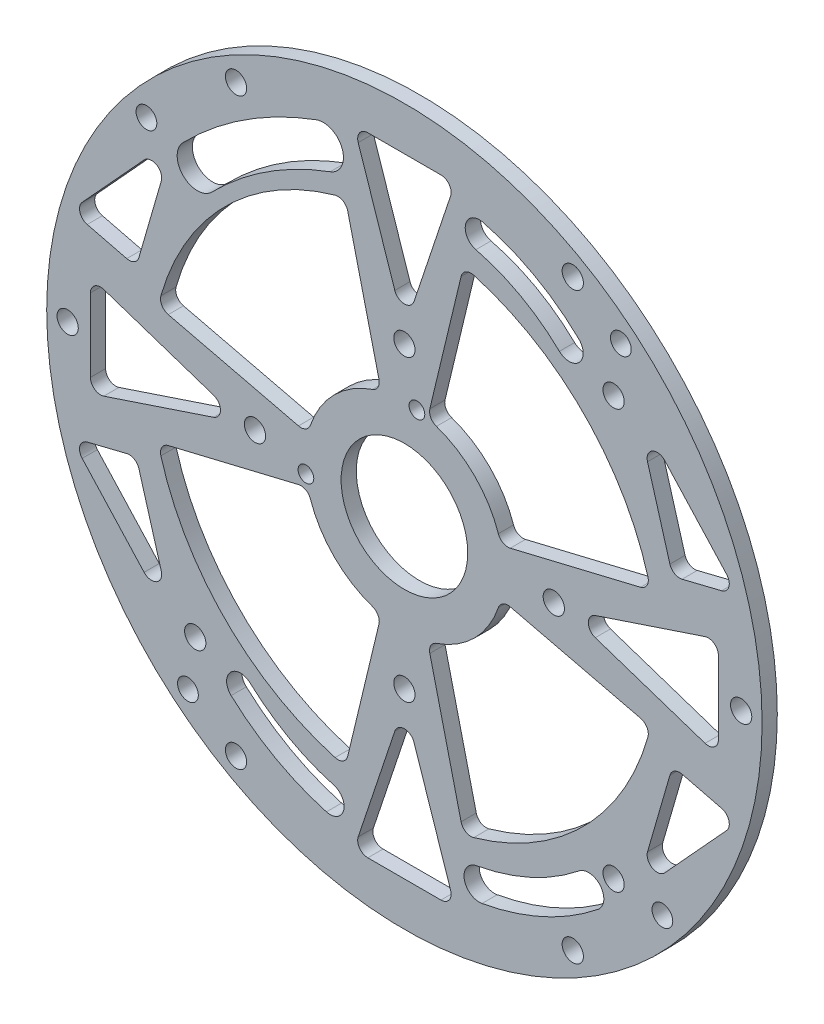
SolidWorks part; units mm, degrees
material "Hexcel AS4C (3000 丝)"
ref_plane "前视基准面" through (0, 0, 0) normal (0, 0, 1) x (1, 0, 0)
ref_plane "上视基准面" through (0, 0, 0) normal (0, 1, 0) x (1, 0, 0)
ref_plane "右视基准面" through (0, 0, 0) normal (1, 0, 0) x (0, 0, -1)
other "Configuration Table"
sketch "草图1" plane through (0, 0, 0) normal (0, 0, 1) x (1, 0, 0)
  line L0 (0, 0) -> (0, -12) construction
  line L1 (-20.8597, -20.8597) -> (20.8597, -20.8597) construction
  line L2 (-20.8597, -20.8597) -> (-20.8597, 20.8597) construction
  line L3 (-20.8597, 20.8597) -> (20.8597, 20.8597) construction
  line L4 (20.8597, -20.8597) -> (20.8597, 20.8597) construction
  line L5 (-20.8597, -20.8597) -> (20.8597, 20.8597) construction
  line L6 (-20.8597, 20.8597) -> (20.8597, -20.8597) construction
  line L7 (-14, -12) -> (14, -12) construction
  line L8 (0, 0) -> (49.95, 49.95) construction
  line L9 (0, 0) -> (70.64, 0) construction
  line L10 (0, 0) -> (0, 70.64) construction
  circle A0 centre (0, 0) radius 29.5 construction
  circle A2 centre (0, 0) radius 66.5 construction
  circle A11 centre (41.3082, 41.3082) radius 2.1
  circle A13 centre (33.25, 57.5907) radius 2.1
  circle A14 centre (66.5, 0) radius 2.1
  circle A15 centre (33.25, -57.5907) radius 2.1
  circle A16 centre (-33.25, -57.5907) radius 2.1
  circle A17 centre (-66.5, 0) radius 2.1
  circle A18 centre (-33.25, 57.5907) radius 2.1
  circle A19 centre (0, 0) radius 70.64
  circle A20 centre (47.0226, 47.0226) radius 2.1 construction
  circle A23 centre (-47.0226, 47.0226) radius 2.1 construction
  circle A24 centre (47.0226, -47.0226) radius 2.1 construction
  circle A25 centre (-47.0226, -47.0226) radius 2.1 construction
  circle A26 centre (41.3082, -41.3082) radius 2.1
  circle A27 centre (-41.3082, -41.3082) radius 2.1
  circle A28 centre (0, -29.5) radius 2.1
  circle A29 centre (-29.5, 0) radius 2.1
  circle A30 centre (0, 29.5) radius 2.1
  circle A31 centre (29.5, 0) radius 2.1
  circle A32 centre (2.4749, 19.4454) radius 1.55
  circle A33 centre (-19.4454, -2.4749) radius 1.55
  circle A34 centre (-19.4454, -2.4749) radius 1.5 construction
  circle A35 centre (2.4749, 19.4454) radius 2.74 construction
  point P17 (0, -12)
  point P29 (0, 0)
  point P30 (0, 0)
  point P43 (0, 0)
  point P53 (0, 0)
  dimension "D1" = 59
  dimension "D2" = 4.2
  dimension "D5" = 4.2
  dimension "D6" = 4.2
  dimension "D7" = 4.2
  dimension "D9" = 133
  dimension "D10" = 4.2
  dimension "D12" = 141.28
  dimension "D14" = 4.2
  dimension "D8" = 3.1
  dimension "D3" = 12
  dimension "D4" = 28
  dimension "D13" = 45
  dimension "D11" = 6
extrude "凸台-拉伸1" add sketch "草图1" along normal blind 3
sketch "草图2" plane through (0, 0, 3) normal (0, 0, 1) x (1, 0, 0)
  circle A0 centre (0, 0) radius 12.5
  dimension "D1" = 25
extrude "切除-拉伸1" cut sketch "草图2" against normal through all
sketch "草图3" [suppressed] plane through (0, 0, 3) normal (0, 0, 1) x (1, 0, 0)
  line L0 (0, 0) -> (0, 70.64) construction
  line L1 (0, 0) -> (70.64, 0) construction
  circle A0 centre (0, 0) radius 70.64 construction
  circle A1 centre (12.5, 0) radius 1.1
  circle A2 centre (-12.5, 0) radius 1.1
  circle A3 centre (0, 0) radius 29 construction
  circle A4 centre (0, 29) radius 2.1 construction
  circle A5 centre (25.1147, -14.5) radius 2.1 construction
  circle A6 centre (-25.1147, -14.5) radius 2.1 construction
  point P21 (0, 0)
  dimension "D1" = 2.2
  dimension "D2" = 25
  dimension "D3" = 58
  dimension "D4" = 4.2
  dimension "D5" = 3
sketch "草图4" plane through (0, 0, 0) normal (0, 0, -1) x (-1, 0, 0)
  circle A0 centre (0, 0) radius 29.5 construction
  circle A1 centre (29.5, 0) radius 2.1
  circle A2 centre (0, -29.5) radius 2.1
  circle A3 centre (-29.5, 0) radius 2.1
  circle A4 centre (0, 29.5) radius 2.1
  point P14 (0, 0)
  dimension "D1" = 59
  dimension "D2" = 4.2
sketch "草图5" plane through (0, 0, 3) normal (0, 0, 1) x (1, 0, 0)
  line L0 (0, 0) -> (-66.5, 0) construction
  line L1 (0, 0) -> (-33.25, 57.5907) construction
  line L3 (0, 0) -> (-50.942, 42.7454) construction
  circle A0 centre (0, 0) radius 66.5 construction
  circle A1 centre (-50.942, 42.7454) radius 2.05
  circle A2 centre (42.7454, 50.942) radius 2.05
  circle A3 centre (50.942, -42.7454) radius 2.05
  circle A4 centre (-42.7454, -50.942) radius 2.05
  point P18 (0, 0)
  dimension "D1" = 133
  dimension "D3" = 4.1
  dimension "D2" = 40
extrude "切除-拉伸2" cut sketch "草图5" against normal through all
sketch "草图6" plane through (0, 0, 3) normal (0, 0, 1) x (1, 0, 0)
  line L0 (0, 0) -> (-35.3553, 35.3553) construction
  line L1 (0, 0) -> (-50, 0) construction
  line L2 (-4.5761, 19.0607) -> (-11.6723, 48.6185)
  line L3 (-19.0607, 4.5761) -> (-48.6185, 11.6723)
  line L4 (19.0607, 4.5761) -> (48.6185, 11.6723)
  line L5 (4.5761, 19.0607) -> (11.6723, 48.6185)
  line L6 (4.5761, -19.0607) -> (11.6723, -48.6185)
  line L7 (19.0607, -4.5761) -> (48.6185, -11.6723)
  line L8 (-19.0607, -4.5761) -> (-48.6185, -11.6723)
  line L9 (-4.5761, -19.0607) -> (-11.6723, -48.6185)
  line L10 (0, 0) -> (0, 70.64) construction
  line L11 (-10, 62) -> (10, 62)
  line L12 (10, 62) -> (0, 32)
  line L13 (0, 32) -> (-10, 62)
  line L14 (32, 0) -> (62, 10)
  line L15 (62, 10) -> (62, -10)
  line L16 (62, -10) -> (32, 0)
  line L17 (0, -32) -> (10, -62)
  line L18 (10, -62) -> (-10, -62)
  line L19 (-10, -62) -> (0, -32)
  line L20 (-32, 0) -> (-62, -10)
  line L21 (-62, -10) -> (-62, 10)
  line L22 (-62, 10) -> (-32, 0)
  line L23 (52.9621, -16.2095) -> (65.904, -19.4141)
  line L24 (65.904, -19.4141) -> (45.635, -41.5681)
  line L25 (45.635, -41.5681) -> (52.9621, -16.2095)
  line L26 (65.904, 19.4141) -> (45.635, 41.5681)
  line L27 (52.9621, 16.2095) -> (65.904, 19.4141)
  line L28 (45.635, 41.5681) -> (52.9621, 16.2095)
  line L29 (-52.9621, 16.2095) -> (-65.904, 19.4141)
  line L30 (-45.635, 41.5681) -> (-52.9621, 16.2095)
  line L31 (-65.904, 19.4141) -> (-45.635, 41.5681)
  line L32 (-65.904, -19.4141) -> (-45.635, -41.5681)
  line L33 (-52.9621, -16.2095) -> (-65.904, -19.4141)
  line L34 (-45.635, -41.5681) -> (-52.9621, -16.2095)
  arc A0 (-11.6723, 48.6185) -> (-48.6185, 11.6723) centre (0, 0) ccw
  arc A1 (-4.5761, 19.0607) -> (-19.0607, 4.5761) centre (0, 0) ccw
  arc A2 (48.6185, 11.6723) -> (11.6723, 48.6185) centre (0, 0) ccw
  arc A3 (19.0607, 4.5761) -> (4.5761, 19.0607) centre (0, 0) ccw
  arc A4 (11.6723, -48.6185) -> (48.6185, -11.6723) centre (0, 0) ccw
  arc A5 (4.5761, -19.0607) -> (19.0607, -4.5761) centre (0, 0) ccw
  arc A6 (-48.6185, -11.6723) -> (-11.6723, -48.6185) centre (0, 0) ccw
  arc A7 (-19.0607, -4.5761) -> (-4.5761, -19.0607) centre (0, 0) ccw
  circle A9 centre (0, 0) radius 70.64 construction
  point P24 (0, 0)
  point P41 (0, 0)
  dimension "D1" = 100
  dimension "D4" = 30
  dimension "D2" = 45
  dimension "D3" = 63
  dimension "D5" = 20
  dimension "D6" = 32
  dimension "D7" = 4
extrude "切除-拉伸3" cut sketch "草图6" against normal through all
fillet "圆角1" radius 2 40 edges at (10, 62, 1.5) (0, 32, 1.5) (-10, 62, 1.5) (-32, 0, 1.5) (-62, -10, 1.5) (-62, 10, 1.5) (0, -32, 1.5) (10, -62, 1.5) (-10, -62, 1.5) (32, 0, 1.5) (62, 10, 1.5) (62, -10, 1.5) (-11.6723, -48.6185, 1.5) (-48.6185, -11.6723, 1.5) (-19.0607, -4.5761, 1.5) (-4.5761, -19.0607, 1.5) (48.6185, -11.6723, 1.5) (11.6723, -48.6185, 1.5) (4.5761, -19.0607, 1.5) (19.0607, -4.5761, 1.5) (11.6723, 48.6185, 1.5) (48.6185, 11.6723, 1.5) (19.0607, 4.5761, 1.5) (4.5761, 19.0607, 1.5) (-4.5761, 19.0607, 1.5) (-19.0607, 4.5761, 1.5) (-48.6185, 11.6723, 1.5) (-11.6723, 48.6185, 1.5) (-45.635, -41.5681, 1.5) (-65.904, -19.4141, 1.5) (45.635, 41.5681, 1.5) (65.904, 19.4141, 1.5) (52.9621, 16.2095, 1.5) (65.904, -19.4141, 1.5) (45.635, -41.5681, 1.5) (52.9621, -16.2095, 1.5) (-52.9621, -16.2095, 1.5) (-65.904, 19.4141, 1.5) (-52.9621, 16.2095, 1.5) (-45.635, 41.5681, 1.5)
sketch "草图7" plane through (0, 0, 3) normal (0, 0, 1) x (1, 0, 0)
  line L0 (0, 0) -> (0, 82.0286) construction
  arc A0 (-40.8733, 39.2537) -> (-16.0408, 55.3643) centre (7.1078, -7.5098) cw construction
  arc A1 (-17.4228, 59.118) -> (-43.7378, 42.0456) centre (7.1078, -7.5098) ccw
  arc A2 (-14.6588, 51.6106) -> (-38.0087, 36.4619) centre (7.1078, -7.5098) ccw
  arc A3 (-14.6588, 51.6106) -> (-17.4228, 59.118) centre (-16.0408, 55.3643) ccw
  arc A4 (-43.7378, 42.0456) -> (-38.0087, 36.4619) centre (-40.8733, 39.2537) ccw
  arc A5 (14.7852, 55.3643) -> (32.5352, 45.5344) centre (5.2005, 17.1165) cw construction
  arc A10 (-32.3601, -45.7303) -> (-14.6588, -55.5825) centre (-2.9999, -13.807) ccw construction
  arc A11 (34.4604, 47.5359) -> (15.4602, 58.0582) centre (5.2005, 17.1165) ccw
  arc A12 (30.61, 43.5329) -> (14.1101, 52.6704) centre (5.2005, 17.1165) ccw
  arc A13 (30.61, 43.5329) -> (34.4604, 47.5359) centre (32.5352, 45.5344) ccw
  arc A14 (15.4602, 58.0582) -> (14.1101, 52.6704) centre (14.7852, 55.3643) ccw
  arc A15 (-34.2204, -47.753) -> (-15.3975, -58.2295) centre (-2.9999, -13.807) ccw
  arc A16 (-30.4998, -43.7076) -> (-13.92, -52.9356) centre (-2.9999, -13.807) ccw
  arc A17 (-30.4998, -43.7076) -> (-34.2204, -47.753) centre (-32.3601, -45.7303) ccw
  arc A18 (-15.3975, -58.2295) -> (-13.92, -52.9356) centre (-14.6588, -55.5825) ccw
  arc A19 (14.7852, -55.5825) -> (36.3718, -45.7303) centre (6.1578, -8.1047) ccw construction
  arc A20 (15.3232, -58.5433) -> (38.256, -48.0767) centre (6.1578, -8.1047) ccw
  arc A21 (14.2471, -52.6217) -> (34.4876, -43.3839) centre (6.1578, -8.1047) ccw
  arc A22 (14.2471, -52.6217) -> (15.3232, -58.5433) centre (14.7852, -55.5825) ccw
  arc A23 (38.256, -48.0767) -> (34.4876, -43.3839) centre (36.3718, -45.7303) ccw
  point P3 (-29.3579, 48.6975)
  point P11 (24.3033, 51.6106)
  point P22 (-24.0927, -51.7044)
  point P30 (26.1935, -52.004)
  dimension "D3" = 4
  dimension "D1" = 30
extrude "切除-拉伸4" cut sketch "草图7" against normal through all
